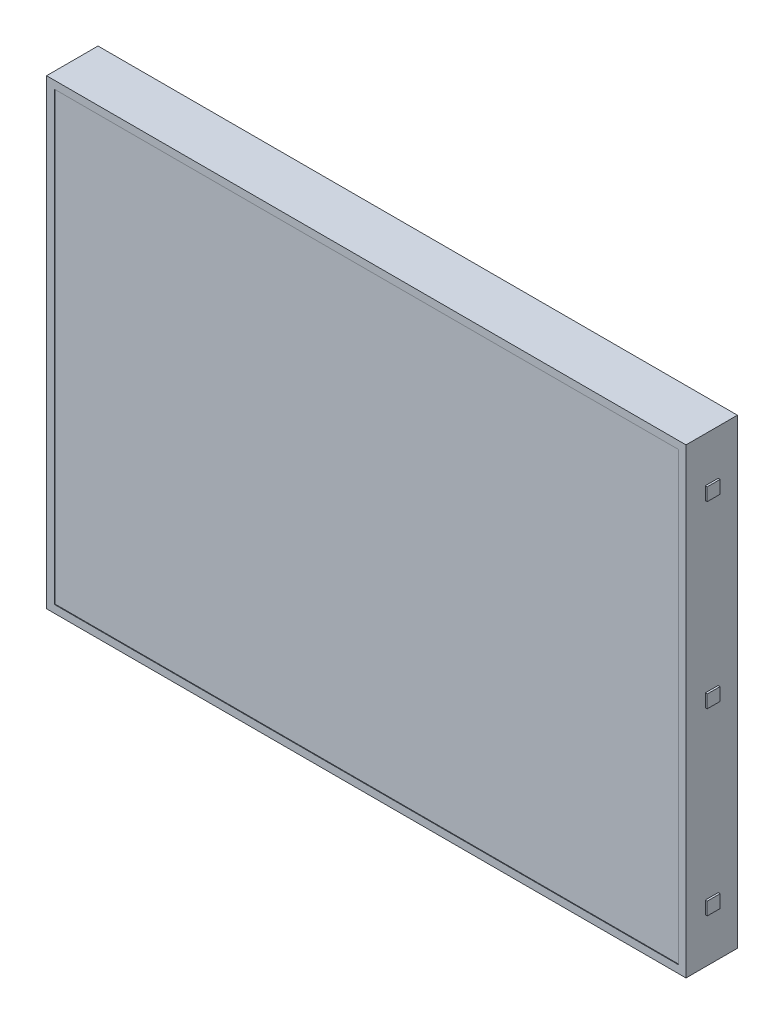
SolidWorks part; units mm, degrees
ref_plane "Front Plane" through (0, 0, 0) normal (0, 0, 1) x (1, 0, 0)
ref_plane "Top Plane" through (0, 0, 0) normal (0, 1, 0) x (1, 0, 0)
ref_plane "Right Plane" through (0, 0, 0) normal (1, 0, 0) x (0, 0, -1)
sketch "Sketch1" plane through (0, 0, 0) normal (0, 0, 1) x (1, 0, 0)
  line L1 (124.3, 89.75) -> (-124.3, 89.75)
  line L2 (124.3, 89.75) -> (124.3, -89.75)
  line L3 (124.3, -89.75) -> (-124.3, -89.75)
  line L4 (-124.3, 89.75) -> (-124.3, -89.75)
  line L5 (124.3, 89.75) -> (-124.3, -89.75) construction
  line L6 (124.3, -89.75) -> (-124.3, 89.75) construction
  point P0 (0, 0)
  dimension "D1" = 248.6
  dimension "D2" = 179.5
extrude "Boss-Extrude1" add sketch "Sketch1" along normal blind 20
ref_plane "Plane1" through (0, 0, 20) normal (0, 0, 1) x (1, 0, 0)
sketch "Sketch2" plane through (0, 0, 20) normal (0, 0, 1) x (1, 0, 0)
  line L0 (-124.3, 89.75) -> (-124.3, -89.75) construction
  line L1 (121.3, 86.75) -> (-121.3, 86.75)
  line L2 (121.3, 86.75) -> (121.3, -86.75)
  line L3 (121.3, -86.75) -> (-121.3, -86.75)
  line L4 (-121.3, 86.75) -> (-121.3, -86.75)
  line L5 (121.3, 86.75) -> (-121.3, -86.75) construction
  line L6 (121.3, -86.75) -> (-121.3, 86.75) construction
  line L7 (-124.3, -89.75) -> (124.3, -89.75) construction
  line L8 (124.3, -89.75) -> (124.3, 89.75) construction
  line L9 (124.3, 89.75) -> (-124.3, 89.75) construction
  point P0 (0, 0)
  dimension "D1" = 3
  dimension "D2" = 3
  dimension "D3" = 3
  dimension "D4" = 3
extrude "Cut-Extrude1" cut sketch "Sketch2" against normal blind 0.25
ref_plane "Plane2" through (124.3, 0, 0) normal (1, 0, 0) x (0, 0, -1)
sketch "Sketch3" plane through (124.3, 0, 0) normal (1, 0, 0) x (0, 0, -1)
  line L0 (-10, 89.75) -> (-10, -89.75) construction
  line L1 (-20, 89.75) -> (0, 89.75) construction
  line L2 (-20, -89.75) -> (0, -89.75) construction
  line L4 (-7.5, 72.25) -> (-12.5, 72.25)
  line L5 (-7.5, 72.25) -> (-7.5, 67.25)
  line L6 (-7.5, 67.25) -> (-12.5, 67.25)
  line L7 (-12.5, 72.25) -> (-12.5, 67.25)
  line L8 (-7.5, 72.25) -> (-12.5, 67.25) construction
  line L9 (-7.5, 67.25) -> (-12.5, 72.25) construction
  line L10 (-7.5, 2.5) -> (-12.5, 2.5)
  line L11 (-7.5, 2.5) -> (-7.5, -2.5)
  line L12 (-7.5, -2.5) -> (-12.5, -2.5)
  line L13 (-12.5, 2.5) -> (-12.5, -2.5)
  line L14 (-7.5, 2.5) -> (-12.5, -2.5) construction
  line L15 (-7.5, -2.5) -> (-12.5, 2.5) construction
  line L16 (-7.5, -67.25) -> (-12.5, -67.25)
  line L17 (-7.5, -67.25) -> (-7.5, -72.25)
  line L18 (-7.5, -72.25) -> (-12.5, -72.25)
  line L19 (-12.5, -67.25) -> (-12.5, -72.25)
  line L20 (-7.5, -67.25) -> (-12.5, -72.25) construction
  line L21 (-7.5, -72.25) -> (-12.5, -67.25) construction
  point P6 (-10, 69.75)
  point P11 (-10, 0)
  point P16 (-10, -69.75)
  dimension "D1" = 5
  dimension "D2" = 5
  dimension "D3" = 5
  dimension "D4" = 5
  dimension "D5" = 5
  dimension "D6" = 5
  dimension "D7" = 20
  dimension "D8" = 20
extrude "Boss-Extrude2" add sketch "Sketch3" along normal blind 0.75 contours L5 L4 L7 L6 | L11 L10 L13 L12 | L17 L16 L19 L18
ref_plane "Plane3" through (-124.3, 0, 0) normal (-1, 0, 0) x (0, 0, 1)
sketch "Sketch4" plane through (-124.3, 0, 0) normal (-1, 0, 0) x (0, 0, 1)
  line L0 (10, 89.75) -> (10, -89.75) construction
  line L1 (20, 89.75) -> (0, 89.75) construction
  line L2 (20, -89.75) -> (0, -89.75) construction
  circle A0 centre (10, 81.6317) radius 2.75
  dimension "D1" = 5.5
extrude "Cut-Extrude2" cut sketch "Sketch4" against normal blind 9
ref_plane "Plane4" through (-115.3, 0, 0) normal (-1, 0, 0) x (0, 0, 1)
sketch "Sketch6" plane through (-115.3, 0, 0) normal (-1, 0, 0) x (0, 0, 1)
  line L0 (10, 84.3817) -> (10, 78.8817) construction
  line L1 (12.75, 81.6317) -> (7.25, 81.6317) construction
  circle A0 centre (10, 81.6317) radius 2.75 construction
  circle A1 centre (10, 81.6317) radius 2.75 construction
  circle A2 centre (10, 81.6317) radius 1.05
  dimension "D1" = 2.1
extrude "Boss-Extrude3" add sketch "Sketch6" along normal blind 6
fillet "Fillet1" radius 0.25 1 edges at (-121.3, 80.5817, 10)
